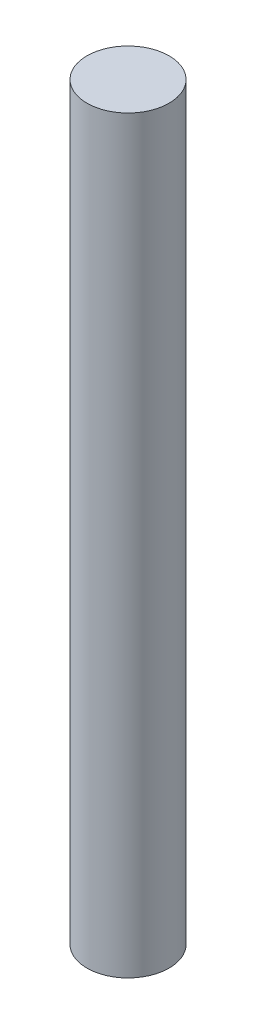
SolidWorks part; units mm, degrees
ref_plane "Front Plane" through (0, 0, 0) normal (0, 0, 1) x (1, 0, 0)
ref_plane "Top Plane" through (0, 0, 0) normal (0, 1, 0) x (1, 0, 0)
ref_plane "Right Plane" through (0, 0, 0) normal (1, 0, 0) x (0, 0, -1)
sketch "Sketch1" plane through (0, 0, 0) normal (0, 1, 0) x (1, 0, 0)
  circle A0 centre (0, 0) radius 1.59
  dimension "D1" = 3.18
extrude "Boss-Extrude1" add sketch "Sketch1" along normal blind 29
